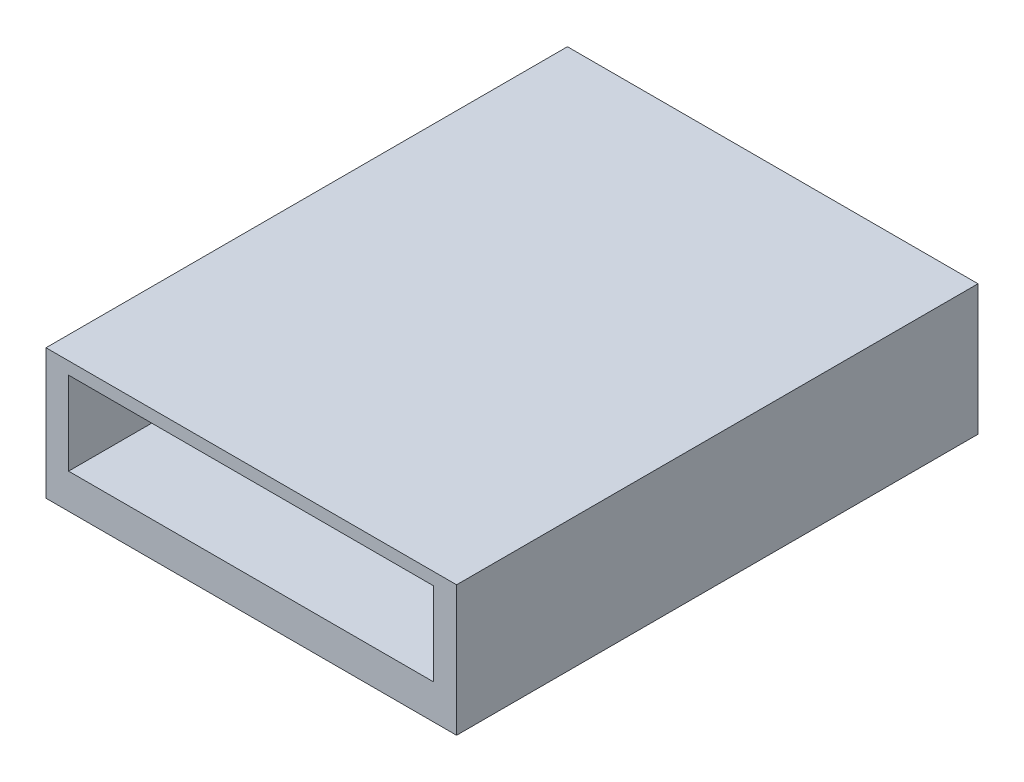
SolidWorks part; units mm, degrees
ref_plane "Front Plane" through (0, 0, 0) normal (0, 0, 1) x (1, 0, 0)
ref_plane "Top Plane" through (0, 0, 0) normal (0, 1, 0) x (1, 0, 0)
ref_plane "Right Plane" through (0, 0, 0) normal (1, 0, 0) x (0, 0, -1)
sketch "Sketch1" plane through (0, 0, 0) normal (0, 0, 1) x (1, 0, 0)
  line L1 (0, 0) -> (12, 0)
  line L2 (0, 0) -> (0, 3.81)
  line L3 (0, 3.81) -> (12, 3.81)
  line L4 (12, 0) -> (12, 3.81)
  dimension "D1" = 12
  dimension "D2" = 3.81
extrude "Boss-Extrude1" add sketch "Sketch1" against normal blind 15.24
sketch "Sketch2" plane through (0, 0, 0) normal (0, 0, 1) x (1, 0, 0)
  line L0 (0, 3.81) -> (0, 0) construction
  line L1 (0.6604, 3.447) -> (11.3284, 3.447)
  line L2 (0.6604, 3.447) -> (0.6604, 1.016)
  line L3 (0.6604, 1.016) -> (11.3284, 1.016)
  line L4 (11.3284, 3.447) -> (11.3284, 1.016)
  line L5 (12, 0) -> (12, 3.81) construction
  line L6 (0, 0) -> (12, 0) construction
  dimension "D1" = 10.668
  dimension "D2" = 0.6604
  dimension "D3" = 0.6716
  dimension "D4" = 1.016
extrude "Cut-Extrude1" cut sketch "Sketch2" against normal blind 12.7
